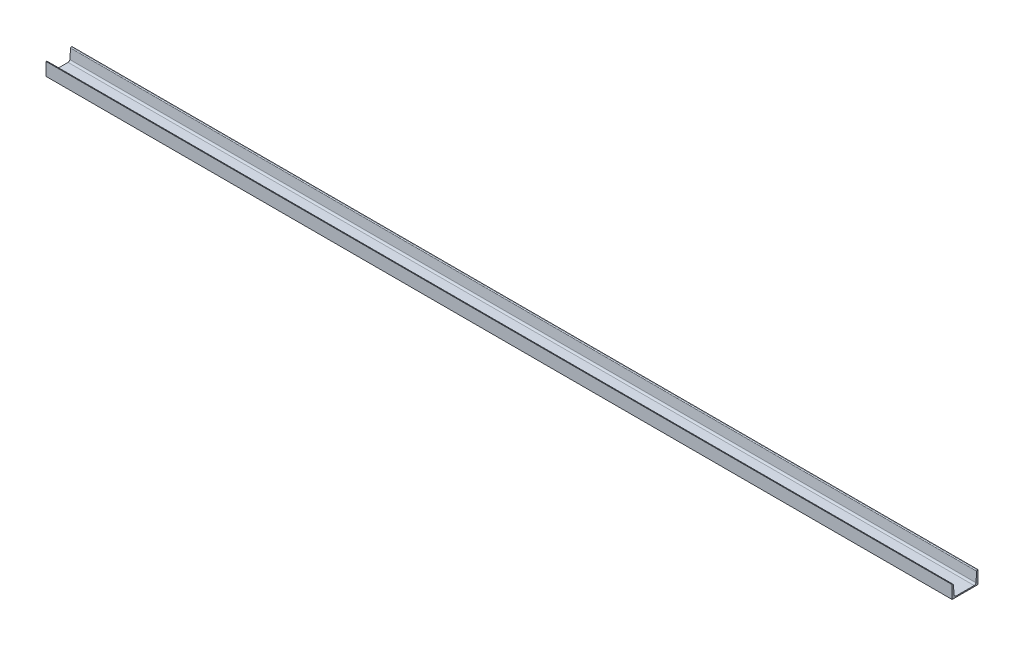
SolidWorks part; units mm, degrees
material "1.0037 (S235JR)"
ref_plane "Ön Düzlem" through (0, 0, 0) normal (0, 0, 1) x (1, 0, 0)
ref_plane "Üst Düzlem" through (0, 0, 0) normal (0, 1, 0) x (1, 0, 0)
ref_plane "Sağ Düzlem" through (0, 0, 0) normal (1, 0, 0) x (0, 0, -1)
sketch "Çizim1" plane through (0, 0, 0) normal (0, 0, 1) x (1, 0, 0)
  line L0 (0, 0) -> (5250, 0)
  dimension "D1" = 5250
other "C kanal C 150 X 75 X 6.5(1)"
ref_plane "Düzlem1" through (0, 0, 0) normal (1, 0, 0) x (0, 1, 0)
sketch "Sketch1" plane through (0, 0, 0) normal (1, 0, 0) x (0, 1, 0)
  line L0 (75, 150) -> (0, 150)
  line L1 (75, 0) -> (0, 0)
  line L2 (0, 150) -> (0, 0)
  line L5 (0, 10) -> (40.75, 10) construction
  line L6 (75, 150) -> (75, 147.5781)
  line L7 (75, 0) -> (75, 2.4219)
  line L8 (6.5, 75) -> (0, 75) construction
  line L12 (6.5, 127.8402) -> (6.5, 22.1598)
  line L17 (15.6284, 137.8021) -> (70.4358, 142.5972)
  line L18 (15.6284, 12.1979) -> (70.4358, 7.4028)
  arc A0 (70.4358, 142.5972) -> (75, 147.5781) centre (70, 147.5781) ccw
  arc A1 (70.4358, 7.4028) -> (75, 2.4219) centre (70, 2.4219) cw
  arc A9 (6.5, 22.1598) -> (15.6284, 12.1979) centre (16.5, 22.1598) ccw
  arc A10 (6.5, 127.8402) -> (15.6284, 137.8021) centre (16.5, 127.8402) cw
  point P10 (37.5, 150)
  point P11 (37.5, 0)
  point P14 (3.25, 75)
  point P15 (0, 0)
  dimension "D4" = 34.25
  dimension "RI" = 10
  dimension "D2" = 5
  dimension "RA" = 5
  dimension "Depth" = 150
  dimension "BF" = 75
  dimension "TW" = 6.5
  dimension "TF" = 10
